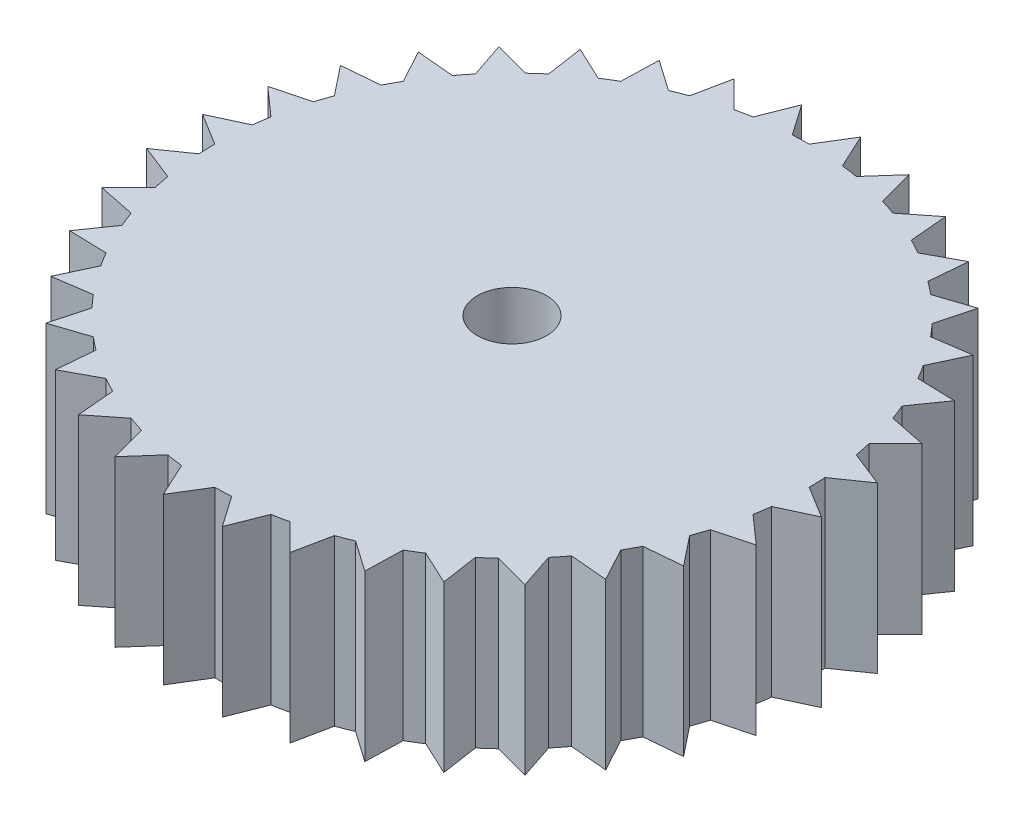
SolidWorks part; units mm, degrees
ref_plane "Front Plane" through (0, 0, 0) normal (0, 0, 1) x (1, 0, 0)
ref_plane "Top Plane" through (0, 0, 0) normal (0, 1, 0) x (1, 0, 0)
ref_plane "Right Plane" through (0, 0, 0) normal (1, 0, 0) x (0, 0, -1)
sketch "Sketch1" plane through (0, 0, 0) normal (0, 1, 0) x (1, 0, 0)
  circle A1 centre (0, 0) radius 9
  dimension "D1" = 18
extrude "Boss-Extrude1" add sketch "Sketch1" along normal blind 5
sketch "Sketch2" plane through (0, 0, 0) normal (0, -1, 0) x (1, 0, 0)
  circle A0 centre (0, 0) radius 2.5
  dimension "D1" = 5
extrude "Cut-Extrude1" cut sketch "Sketch2" against normal blind 3 draft 3
sketch "Sketch3" plane through (0, 3, 0) normal (0, -1, 0) x (1, 0, 0)
  circle A0 centre (0, 0) radius 1.05
  dimension "D1" = 2.1
extrude "Cut-Extrude2" cut sketch "Sketch3" against normal blind 3
sketch "Sketch4" plane through (0, 5, 0) normal (0, 1, 0) x (1, 0, 0)
  line L0 (0, 9) -> (0.5939, 9.9663)
  line L1 (0.5939, 9.9663) -> (1.0733, 8.9358)
  line L2 (1.0733, 8.9358) -> (0, 9)
  line L3 (1.5628, 8.8633) -> (2.3155, 9.7117)
  line L4 (2.3155, 9.7117) -> (2.6087, 8.6136)
  line L5 (2.6087, 8.6136) -> (1.5628, 8.8633)
  line L6 (3.0782, 8.4572) -> (3.9667, 9.1621)
  line L7 (3.9667, 9.1621) -> (4.0648, 8.0298)
  line L8 (4.0648, 8.0298) -> (3.0782, 8.4572)
  line L9 (4.5, 7.7942) -> (5.4974, 8.3341)
  line L10 (5.4974, 8.3341) -> (5.3974, 7.2019)
  line L11 (5.3974, 7.2019) -> (4.5, 7.7942)
  line L12 (5.7851, 6.8944) -> (6.8611, 7.2529)
  line L13 (6.8611, 7.2529) -> (6.566, 6.1553)
  line L14 (6.566, 6.1553) -> (5.7851, 6.8944)
  line L15 (6.8944, 5.7851) -> (8.0163, 5.9513)
  line L16 (8.0163, 5.9513) -> (7.5351, 4.9216)
  line L17 (7.5351, 4.9216) -> (6.8944, 5.7851)
  line L18 (7.7942, 4.5) -> (8.928, 4.4688)
  line L19 (8.928, 4.4688) -> (8.2753, 3.5384)
  line L20 (8.2753, 3.5384) -> (7.7942, 4.5)
  line L21 (8.4572, 3.0782) -> (9.5683, 2.8506)
  line L22 (9.5683, 2.8506) -> (8.764, 2.0476)
  line L23 (8.764, 2.0476) -> (8.4572, 3.0782)
  line L24 (8.8633, 1.5628) -> (9.918, 1.1458)
  line L25 (9.918, 1.1458) -> (8.9864, 0.4947)
  line L26 (8.9864, 0.4947) -> (8.8633, 1.5628)
  line L27 (9, 0) -> (9.9663, -0.5939)
  line L28 (9.9663, -0.5939) -> (8.9358, -1.0733)
  line L29 (8.9358, -1.0733) -> (9, 0)
  line L30 (8.8633, -1.5628) -> (9.7117, -2.3155)
  line L31 (9.7117, -2.3155) -> (8.6136, -2.6087)
  line L32 (8.6136, -2.6087) -> (8.8633, -1.5628)
  line L33 (8.4572, -3.0782) -> (9.1621, -3.9667)
  line L34 (9.1621, -3.9667) -> (8.0298, -4.0648)
  line L35 (8.0298, -4.0648) -> (8.4572, -3.0782)
  line L36 (7.7942, -4.5) -> (8.3341, -5.4974)
  line L37 (8.3341, -5.4974) -> (7.2019, -5.3974)
  line L38 (7.2019, -5.3974) -> (7.7942, -4.5)
  line L39 (6.8944, -5.7851) -> (7.2529, -6.8611)
  line L40 (7.2529, -6.8611) -> (6.1553, -6.566)
  line L41 (6.1553, -6.566) -> (6.8944, -5.7851)
  line L42 (5.7851, -6.8944) -> (5.9513, -8.0163)
  line L43 (5.9513, -8.0163) -> (4.9216, -7.5351)
  line L44 (4.9216, -7.5351) -> (5.7851, -6.8944)
  line L45 (4.5, -7.7942) -> (4.4688, -8.928)
  line L46 (4.4688, -8.928) -> (3.5384, -8.2753)
  line L47 (3.5384, -8.2753) -> (4.5, -7.7942)
  line L48 (3.0782, -8.4572) -> (2.8506, -9.5683)
  line L49 (2.8506, -9.5683) -> (2.0476, -8.764)
  line L50 (2.0476, -8.764) -> (3.0782, -8.4572)
  line L51 (1.5628, -8.8633) -> (1.1458, -9.918)
  line L52 (1.1458, -9.918) -> (0.4947, -8.9864)
  line L53 (0.4947, -8.9864) -> (1.5628, -8.8633)
  line L54 (0, -9) -> (-0.5939, -9.9663)
  line L55 (-0.5939, -9.9663) -> (-1.0733, -8.9358)
  line L56 (-1.0733, -8.9358) -> (0, -9)
  line L57 (-1.5628, -8.8633) -> (-2.3155, -9.7117)
  line L58 (-2.3155, -9.7117) -> (-2.6087, -8.6136)
  line L59 (-2.6087, -8.6136) -> (-1.5628, -8.8633)
  line L60 (-3.0782, -8.4572) -> (-3.9667, -9.1621)
  line L61 (-3.9667, -9.1621) -> (-4.0648, -8.0298)
  line L62 (-4.0648, -8.0298) -> (-3.0782, -8.4572)
  line L63 (-4.5, -7.7942) -> (-5.4974, -8.3341)
  line L64 (-5.4974, -8.3341) -> (-5.3974, -7.2019)
  line L65 (-5.3974, -7.2019) -> (-4.5, -7.7942)
  line L66 (-5.7851, -6.8944) -> (-6.8611, -7.2529)
  line L67 (-6.8611, -7.2529) -> (-6.566, -6.1553)
  line L68 (-6.566, -6.1553) -> (-5.7851, -6.8944)
  line L69 (-6.8944, -5.7851) -> (-8.0163, -5.9513)
  line L70 (-8.0163, -5.9513) -> (-7.5351, -4.9216)
  line L71 (-7.5351, -4.9216) -> (-6.8944, -5.7851)
  line L72 (-7.7942, -4.5) -> (-8.928, -4.4688)
  line L73 (-8.928, -4.4688) -> (-8.2753, -3.5384)
  line L74 (-8.2753, -3.5384) -> (-7.7942, -4.5)
  line L75 (-8.4572, -3.0782) -> (-9.5683, -2.8506)
  line L76 (-9.5683, -2.8506) -> (-8.764, -2.0476)
  line L77 (-8.764, -2.0476) -> (-8.4572, -3.0782)
  line L78 (-8.8633, -1.5628) -> (-9.918, -1.1458)
  line L79 (-9.918, -1.1458) -> (-8.9864, -0.4947)
  line L80 (-8.9864, -0.4947) -> (-8.8633, -1.5628)
  line L81 (-9, 0) -> (-9.9663, 0.5939)
  line L82 (-9.9663, 0.5939) -> (-8.9358, 1.0733)
  line L83 (-8.9358, 1.0733) -> (-9, 0)
  line L84 (-8.8633, 1.5628) -> (-9.7117, 2.3155)
  line L85 (-9.7117, 2.3155) -> (-8.6136, 2.6087)
  line L86 (-8.6136, 2.6087) -> (-8.8633, 1.5628)
  line L87 (-8.4572, 3.0782) -> (-9.1621, 3.9667)
  line L88 (-9.1621, 3.9667) -> (-8.0298, 4.0648)
  line L89 (-8.0298, 4.0648) -> (-8.4572, 3.0782)
  line L90 (-7.7942, 4.5) -> (-8.3341, 5.4974)
  line L91 (-8.3341, 5.4974) -> (-7.2019, 5.3974)
  line L92 (-7.2019, 5.3974) -> (-7.7942, 4.5)
  line L93 (-6.8944, 5.7851) -> (-7.2529, 6.8611)
  line L94 (-7.2529, 6.8611) -> (-6.1553, 6.566)
  line L95 (-6.1553, 6.566) -> (-6.8944, 5.7851)
  line L96 (-5.7851, 6.8944) -> (-5.9513, 8.0163)
  line L97 (-5.9513, 8.0163) -> (-4.9216, 7.5351)
  line L98 (-4.9216, 7.5351) -> (-5.7851, 6.8944)
  line L99 (-4.5, 7.7942) -> (-4.4688, 8.928)
  line L100 (-4.4688, 8.928) -> (-3.5384, 8.2753)
  line L101 (-3.5384, 8.2753) -> (-4.5, 7.7942)
  line L102 (-3.0782, 8.4572) -> (-2.8506, 9.5683)
  line L103 (-2.8506, 9.5683) -> (-2.0476, 8.764)
  line L104 (-2.0476, 8.764) -> (-3.0782, 8.4572)
  line L105 (-1.5628, 8.8633) -> (-1.1458, 9.918)
  line L106 (-1.1458, 9.918) -> (-0.4947, 8.9864)
  line L107 (-0.4947, 8.9864) -> (-1.5628, 8.8633)
  line L108 (0, 0) -> (1.0733, 8.9358) construction
  line L109 (0, 0) -> (2.6087, 8.6136) construction
  circle A0 centre (0, 0) radius 9 construction
  dimension "D1" = 1
  dimension "D2" = 61.85
  dimension "D3" = 36
  dimension "D4" = 10
extrude "Boss-Extrude2" add sketch "Sketch4" against normal blind 5
